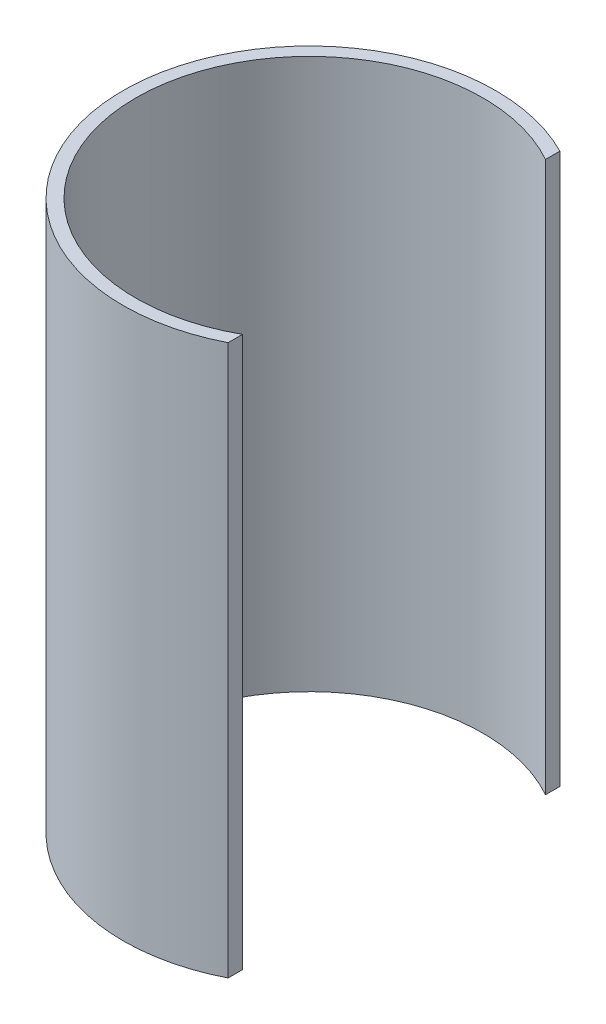
SolidWorks part; units mm, degrees
ref_plane "前视基准面" through (0, 0, 0) normal (0, 0, 1) x (1, 0, 0)
ref_plane "上视基准面" through (0, 0, 0) normal (0, 1, 0) x (1, 0, 0)
ref_plane "右视基准面" through (0, 0, 0) normal (1, 0, 0) x (0, 0, -1)
sketch "草图1" plane through (0, 0, 0) normal (0, 0, 1) x (1, 0, 0)
  line L0 (0, 76.1415) -> (0, -25.6456) construction
  line L1 (41, 0) -> (44, 0)
  line L2 (41, 0) -> (41, 130)
  line L3 (41, 130) -> (44, 130)
  line L4 (44, 0) -> (44, 130)
  dimension "D1" = 41
  dimension "D2" = 44
  dimension "D3" = 130
revolve "旋转1" add sketch "草图1" angle 360 about L0
sketch "草图2" plane through (0, 0, 0) normal (0, 0, 1) x (1, 0, 0)
  line L0 (41, 130) -> (-41, 130) construction
  line L1 (20, 130) -> (55, 130)
  line L2 (20, 130) -> (20, 0)
  line L3 (20, 0) -> (55, 0)
  line L4 (55, 130) -> (55, 0)
  dimension "D1" = 20
  dimension "D2" = 35
extrude "切除-拉伸1" cut sketch "草图2" against normal through all and the other way through all
